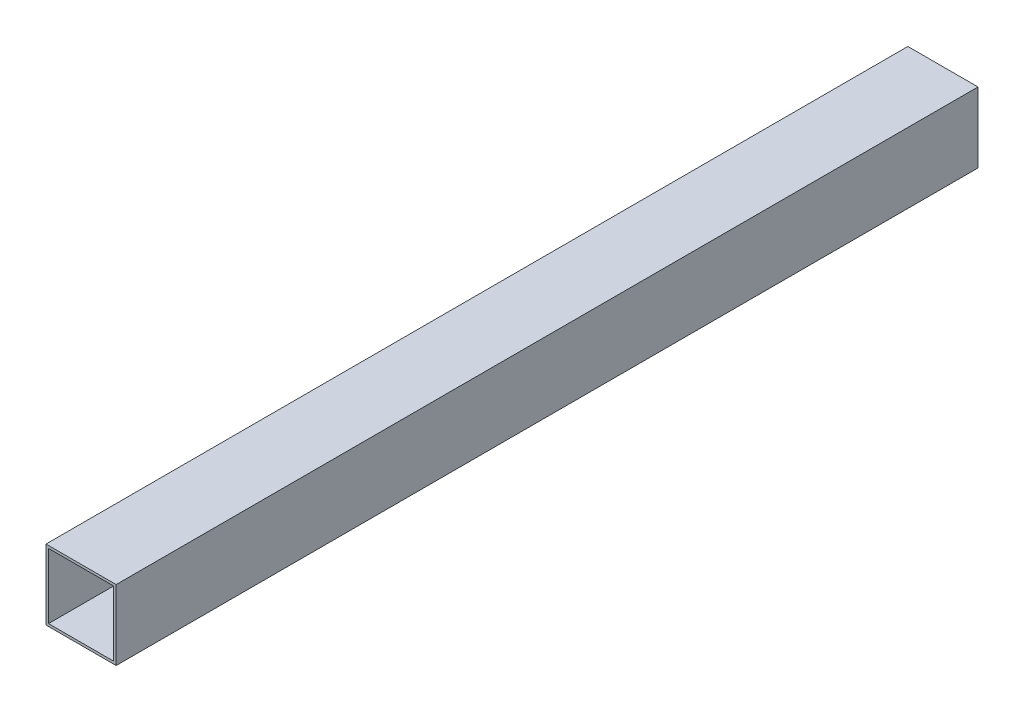
SolidWorks part; units mm, degrees
ref_plane "Alzado" through (0, 0, 0) normal (0, 0, 1) x (1, 0, 0)
ref_plane "Planta" through (0, 0, 0) normal (0, 1, 0) x (1, 0, 0)
ref_plane "Vista lateral" through (0, 0, 0) normal (1, 0, 0) x (0, 0, -1)
sketch "Croquis1" plane through (0, 0, 0) normal (0, 0, 1) x (1, 0, 0)
  line L0 (-32.5, 32.5) -> (-32.5, -32.5)
  line L1 (-35, 35) -> (35, 35)
  line L2 (-35, 35) -> (-35, -35)
  line L3 (-35, -35) -> (35, -35)
  line L4 (35, 35) -> (35, -35)
  line L5 (-35, 35) -> (35, -35) construction
  line L6 (-35, -35) -> (35, 35) construction
  line L7 (-32.5, -32.5) -> (32.5, -32.5)
  line L8 (32.5, 32.5) -> (32.5, -32.5)
  line L9 (-32.5, 32.5) -> (32.5, 32.5)
  point P0 (0, 0)
  dimension "D1" = 70
  dimension "D2" = 70
  dimension "D3" = 2.5
extrude "Saliente-Extruir1" add sketch "Croquis1" along normal mid plane 860
